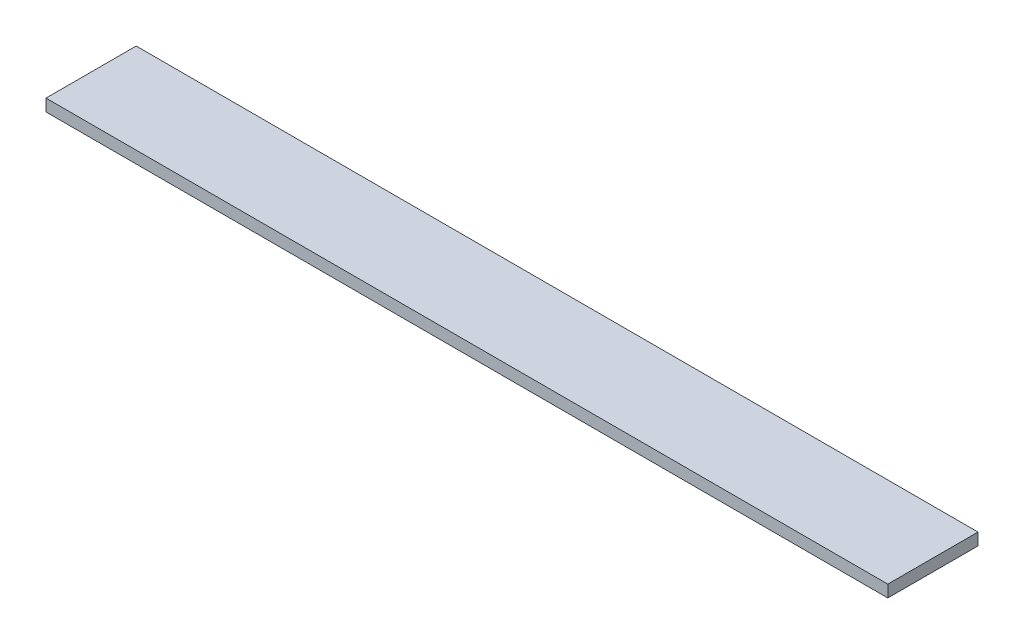
SolidWorks part; units mm, degrees
ref_plane "Front Plane" through (0, 0, 0) normal (0, 0, 1) x (1, 0, 0)
ref_plane "Top Plane" through (0, 0, 0) normal (0, 1, 0) x (1, 0, 0)
ref_plane "Right Plane" through (0, 0, 0) normal (1, 0, 0) x (0, 0, -1)
sketch "Sketch1" plane through (0, 0, 0) normal (0, 1, 0) x (1, 0, 0)
  line L1 (70, -7.5) -> (-70, -7.5)
  line L2 (70, -7.5) -> (70, 7.5)
  line L3 (70, 7.5) -> (-70, 7.5)
  line L4 (-70, -7.5) -> (-70, 7.5)
  line L5 (70, -7.5) -> (-70, 7.5) construction
  line L6 (70, 7.5) -> (-70, -7.5) construction
  point P0 (0, 0)
  dimension "D1" = 15
  dimension "D2" = 140
extrude "Boss-Extrude1" add sketch "Sketch1" along normal blind 2
